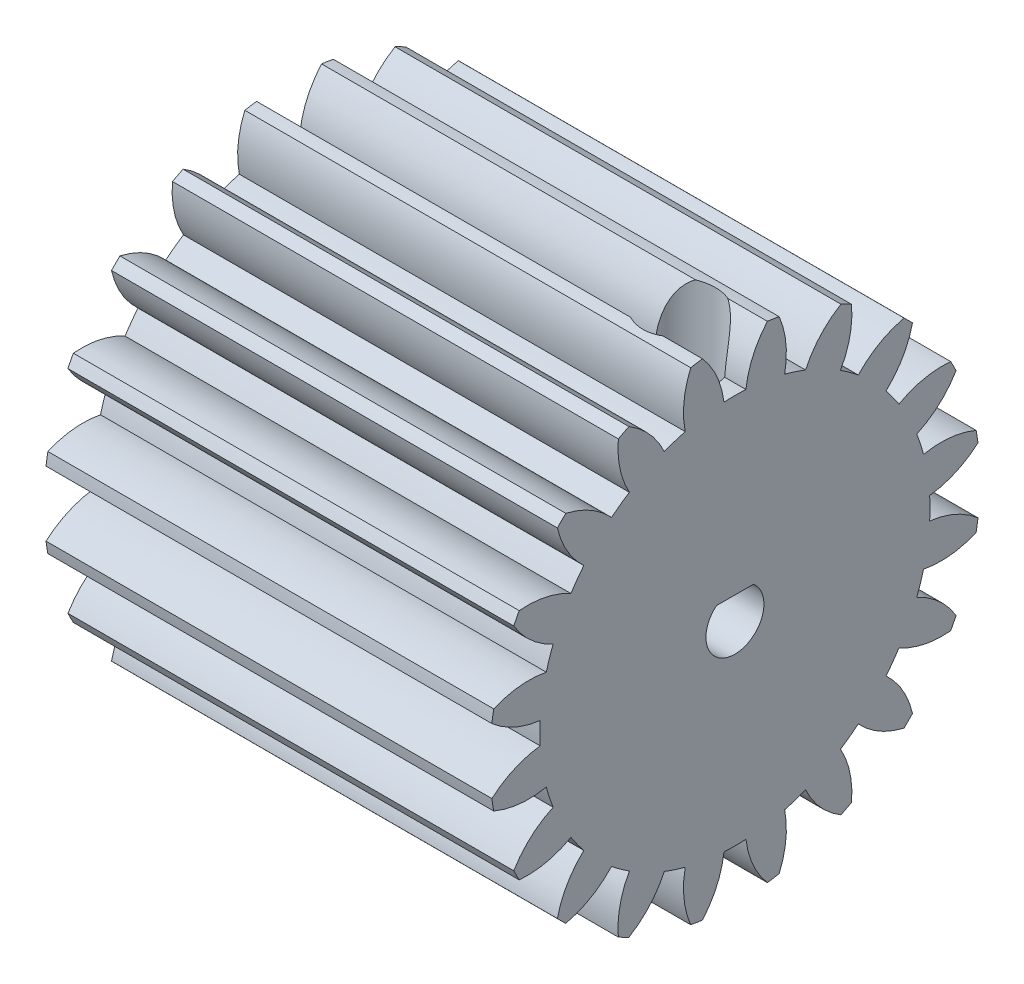
SolidWorks part; units mm, degrees
ref_plane "Plane1" through (0, 0, 0) normal (0, 0, 1) x (1, 0, 0)
ref_plane "Plane2" through (0, 0, 0) normal (0, 1, 0) x (1, 0, 0)
ref_plane "Plane3" through (0, 0, 0) normal (1, 0, 0) x (0, 0, -1)
other "Configuration Table"
sketch "HoldingSke" plane through (0, 0, 0) normal (0, 1, 0) x (1, 0, 0)
  line L0 (0, 0) -> (0.4698, -0.171)
  line L1 (-15, 0) -> (100, 0) construction
  line L2 (0, 0) -> (-2.1039, 2.3779)
  line L3 (0, 0) -> (-11.863, 4.5341)
  line L4 (0, 0) -> (8.1152, 2.9537)
  line L5 (0, 0) -> (-46.8476, -17.4728)
  line L6 (0, 0) -> (-33.1585, -22.3721)
  line L7 (-2.1039, 2.3779) -> (8.6586, 51.2059)
  line L8 (-76.2, 54.61) -> (-76.1, 54.61)
  line L9 (-71.009, 38.7566) -> (-53.1078, 45.2721)
  line L10 (-76.2, 71.12) -> (104.1128, 71.12)
  line L11 (0, 0) -> (-40, 0)
  line L12 (-76.2, 101.6) -> (-76.133, 101.6)
  line L13 (24.9733, 27.94) -> (52.9518, 28.4284)
  line L14 (24.9733, 27.94) -> (24.9743, 27.94)
  line L15 (24.9733, 27.94) -> (100.4006, 29.5858)
  line L16 (-63.627, -2) -> (-12.827, -2)
  circle A0 centre (0, 0) radius 0.4
  circle A1 centre (0, 0) radius 17.499
  circle A2 centre (0, 0) radius 37.5
  circle A3 centre (0, 0) radius 0.4
  dimension "MHD" = 34.998
  dimension "Hub_dia" = 75
  dimension "Bore" = 0.8
  dimension "MBD" = 0.8
  dimension "Num_teeth" = 20
  dimension "Pitch" = 0.5
  dimension "Overall_len" = 50
  dimension "Show_teeth" = 20
  dimension "Thickness" = 40
  dimension "OAL" = 50.0001
  dimension "T_dim" = 0.1
  dimension "Ap" = 20
  dimension "H" = 19.05
  dimension "Pitch_radius" = 180.3128
  dimension "Width" = 40
  dimension "Backlash" = 0.067
  dimension "Addendum_fac" = 1
  dimension "Dedendum_fac" = 1.25
  dimension "Clearance_fac" = 0.25
  dimension "Dedendum_add" = 0.001
  dimension "Module" = 2
sketch "BasProSke" plane through (0, 0, 0) normal (0, 1, 0) x (1, 0, 0)
  line L0 (-10, 0) -> (60, 0) construction
  line L1 (0, 0) -> (0, 22)
  line L2 (0, 0) -> (40, 0)
  line L3 (40, 0) -> (40, 22)
  line L4 (40, 22) -> (0, 22)
  dimension "Thickness" = 40
  dimension "Diameter" = 44
revolve "Base-Revolve" add sketch "BasProSke" angle 360 about L0
sketch "TooCutSke" plane through (0, 0, 0) normal (1, 0, 0) x (0, 0, -1)
  line L1 (0, 0) -> (0, 107) construction
  line L2 (0, 0) -> (-1.6864, 19.9288) construction
  line L3 (0, 0) -> (-6.2409, 39.4033) construction
  line L4 (-1.6864, 19.9288) -> (-3.1204, 19.7016) construction
  arc A0 (0.9862, 17.4712) -> (-0.9862, 17.4712) centre (0, 0) ccw
  arc A1 (2.9329, 21.8293) -> (-2.9329, 21.8293) centre (0, 0) ccw
  circle A2 centre (0, 0) radius 20 construction
  circle A3 centre (0, 0) radius 18.7939 construction
  arc A4 (-0.9862, 17.4712) -> (-2.9329, 21.8293) centre (-8.9313, 16.536) ccw
  arc A5 (2.9329, 21.8293) -> (0.9862, 17.4712) centre (8.9313, 16.536) ccw
  dimension "Root_dia" = 34.998
  dimension "Overcut_dia" = 44.0508
  dimension "Pitch_dia" = 40
  dimension "Base_dia" = 37.5877
  dimension "Flank_rad" = 8
  dimension "Half_ang" = 9
  dimension "Half_CT" = 1.4519
extrude "ToothCut" cut sketch "TooCutSke" along normal through all
fillet "Breaks" [suppressed] radius 0.04
fillet "RootFillets" [suppressed] radius 0.501
pattern_circular "TeethCuts" count 20 every 18 about axis through (-10, 0, 0) along (1, 0, 0) of "ToothCut", "RootFillets", "Breaks"
sketch "HubNeaOneSke" plane through (0, 0, 0) normal (-1, 0, 0) x (0, 0, 1)
  circle A0 centre (0, 0) radius 17.499
  dimension "Diameter" = 34.998
extrude "HubNearOne" [suppressed] add sketch "HubNeaOneSke" along normal blind 10.0001
sketch "HubNeaBotSke" plane through (0, 0, 0) normal (-1, 0, 0) x (0, 0, 1)
  circle A0 centre (0, 0) radius 17.499
  dimension "Diameter" = 34.998
extrude "HubNearBoth" [suppressed] add sketch "HubNeaBotSke" along normal blind 5
ref_plane "FarPln" through (40, 0, 0) normal (1, 0, 0) x (0, 0, -1)
sketch "HubFarSke" plane through (40, 0, 0) normal (1, 0, 0) x (0, 0, -1)
  circle A0 centre (0, 0) radius 17.499
  dimension "Diameter" = 34.998
extrude "HubFar" [suppressed] add sketch "HubFarSke" along normal blind 5
sketch "BorSke" plane through (0, 0, 0) normal (1, 0, 0) x (0, 0, -1)
  circle A0 centre (0, 0) radius 0.4
  dimension "Diameter" = 0.8
extrude "Bore" cut sketch "BorSke" along normal mid plane 100.0001
sketch "KeySke" plane through (0, 0, 0) normal (1, 0, 0) x (0, 0, -1)
  line L0 (-0.05, 0) -> (-0.05, 0.5)
  line L1 (-0.05, 0.5) -> (0.05, 0.5)
  line L2 (0.05, 0.5) -> (0.05, 0)
  line L3 (0, 0) -> (0, 34) construction
  line L4 (-0.05, 0) -> (0.05, 0)
  dimension "Offset" = 0.5
  dimension "Width" = 0.1
extrude "Keyway" [suppressed] cut sketch "KeySke" along normal mid plane 100.0001
pattern_circular "Keyway2" [suppressed] count 2 every 90 about axis through (-10, 0, 0) along (1, 0, 0)
sketch "Sketch1" plane through (40, 0, 0) normal (1, 0, 0) x (0, 0, -1)
  circle A0 centre (0, 0) radius 2.6
  dimension "D1" = 5.2
extrude "Cut-Extrude1" cut sketch "Sketch1" against normal through all
sketch "Sketch2" plane through (0, 0, 0) normal (-1, 0, 0) x (0, 0, 1)
  line L0 (-2.2361, 2) -> (2.2361, 2)
  arc A0 (2.2361, 2) -> (-2.2361, 2) centre (0, 0) ccw
  dimension "D2" = 6
  dimension "D1" = 2
extrude "Boss-Extrude1" add sketch "Sketch2" against normal up to surface (40 mm away) up to face at (40, 0, -2.6)
sketch "Sketch3" plane through (0, 0, 0) normal (-1, 0, 0) x (0, 0, 1)
  line L0 (-1.6613, 2) -> (1.6613, 2) construction
  line L1 (-1.6613, 2) -> (1.6613, 2)
  arc A0 (-1.6613, 2) -> (1.6613, 2) centre (0, 0) ccw construction
  arc A1 (-1.6613, 2) -> (1.6613, 2) centre (0, 0) ccw
extrude "Boss-Extrude2" add sketch "Sketch3" against normal blind 10
ref_plane "Plane4" through (0, 6, 0) normal (0, 1, 0) x (1, 0, 0)
sketch "Sketch4" plane through (0, 6, 0) normal (0, 1, 0) x (1, 0, 0)
  line L0 (40, 0) -> (35, 0) construction
  line L1 (40, -1.6613) -> (40, 1.6613) construction
  circle A0 centre (35, 0) radius 3.25
  dimension "D2" = 6.5
  dimension "D1" = 5
extrude "Cut-Extrude2" cut sketch "Sketch4" along normal through all
sketch "Sketch5" plane through (0, 6, 0) normal (0, 1, 0) x (1, 0, 0)
  circle A0 centre (35, 0) radius 1.4
  dimension "D1" = 2.8
extrude "Cut-Extrude3" cut sketch "Sketch5" against normal up to next
equation "' \"Module@HoldingSke\" = 6.35"
equation "' \"Num_teeth@HoldingSke\" = 12"
equation "' \"Ap@HoldingSke\" =  20"
equation "' \"Ap@HoldingSke\" = 20"
equation "' \"Width@HoldingSke\" = 0.5 * 25.4"
equation "' \"Hub_dia@HoldingSke\"= 1 * 25.4"
equation "' \"Hub_dia@HoldingSke\" = 1 * 25.4"
equation "' \"Overall_len@HoldingSke\" = 1.0 * 25.4"
equation "' \"Bore@HoldingSke\" = 0.75 * 25.4"
equation "' \"T_dim@HoldingSke\" = 0.1 * 25.4"
equation "' \"Width@KeySke\" = 0.25 * 25.4"
equation "' \"Show_teeth@HoldingSke\" = 13"
equation "' \"Backlash@HoldingSke\" = 0.009 * 25.4"
equation "' \"Addendum_fac@HoldingSke\" = 1.0"
equation "' \"Dedendum_fac@HoldingSke\" = 1.25"
equation "' \"Dedendum_add@HoldingSke\" = 0.00005 * 25.4"
equation "' \"Clearance_fac@HoldingSke\" = 0.25"
equation "\"Pitch@HoldingSke\" = 1 / \"Module@HoldingSke\""
equation "\"Overcut_dia@TooCutSke\" = (\"Num_teeth@HoldingSke\" + 2 * \"Addendum_fac@HoldingSke\") / \"Pitch@HoldingSke\" + 0.002 * 25.4"
equation "\"Pitch_dia@TooCutSke\" = \"Num_teeth@HoldingSke\" / \"Pitch@HoldingSke\""
equation "\"Base_dia@TooCutSke\" = \"Num_teeth@HoldingSke\" / \"Pitch@HoldingSke\" * cos((\"Ap@HoldingSke\"  * 3.14159265 / 180))"
equation "\"Root_dia@TooCutSke\" = (\"Num_teeth@HoldingSke\" + 2) / \"Pitch@HoldingSke\" - 2 * (\"Addendum_fac@HoldingSke\" + \"Dedendum_fac@HoldingSke\") / \"Pitch@HoldingSke\" - \"Dedendum_add@HoldingSke\" * 2"
equation "\"Half_ang@TooCutSke\" = 180 / \"Num_teeth@HoldingSke\""
equation "\"Half_CT@TooCutSke\" = \"Num_teeth@HoldingSke\" / \"Pitch@HoldingSke\" * sin((3.14159265 / 2 / \"Num_teeth@HoldingSke\")) / 2 - 7 * \"Backlash@HoldingSke\" / 4"
equation "\"Flank_rad@TooCutSke\" = \"Num_teeth@HoldingSke\" / \"Pitch@HoldingSke\" / 5"
equation "\"Radius@RootFillets\" = \"Clearance_fac@HoldingSke\" / \"Pitch@HoldingSke\" + \"Dedendum_add@HoldingSke\""
equation "\"Break_rad@Breaks\" = 0.02 / \"Pitch@HoldingSke\""
equation "\"Thickness@HoldingSke\" = \"Width@HoldingSke\""
equation "\"OAL@HoldingSke\" = \"Thickness@HoldingSke\""
equation "\"MHD@HoldingSke\" = (\"Num_teeth@HoldingSke\" + 2) / \"Pitch@HoldingSke\" - 2 * (\"Addendum_fac@HoldingSke\" + \"Dedendum_fac@HoldingSke\")  / \"Pitch@HoldingSke\" - \"Dedendum_add@HoldingSke\" * 2"
equation "\"MBD@HoldingSke\" = (\"Num_teeth@HoldingSke\" + 2) / \"Pitch@HoldingSke\" - 2 * (\"Addendum_fac@HoldingSke\" + \"Dedendum_fac@HoldingSke\")  / \"Pitch@HoldingSke\" - \"Dedendum_add@HoldingSke\" * 2 - 0.002 * 25.4"
equation "\"MHD@HoldingSke\" = ((sgn( \"MHD@HoldingSke\" - \"Hub_dia@HoldingSke\" )-1)*( \"MHD@HoldingSke\" - \"Hub_dia@HoldingSke\" ))/-2+ \"Hub_dia@HoldingSke\""
equation "\"MBD@HoldingSke\" = ((sgn( \"MBD@HoldingSke\" - \"Bore@HoldingSke\" )-1)*( \"MBD@HoldingSke\" - \"Bore@HoldingSke\" ))/-2+ \"Bore@HoldingSke\""
equation "\"OAL@HoldingSke\" = ((sgn( \"OAL@HoldingSke\" - \"Overall_len@HoldingSke\" )+1)*( \"OAL@HoldingSke\" - \"Overall_len@HoldingSke\" ))/2 + \"Overall_len@HoldingSke\" + 0.000002 * 25.4"
equation "\"Num_teeth@TeethCuts\" = int( \"Show_teeth@HoldingSke\" ) + 1"
equation "\"Num_teeth@TeethCuts\" = ((sgn( \"Num_teeth@TeethCuts\" - \"Num_teeth@HoldingSke\" )-1)*( \"Num_teeth@TeethCuts\" - \"Num_teeth@HoldingSke\" ))/-2+ \"Num_teeth@HoldingSke\""
equation "\"Num_teeth@TeethCuts\" = ((sgn( \"Num_teeth@TeethCuts\" - 2.0)+1)*( \"Num_teeth@TeethCuts\" - 2.0))/2 +2.0"
equation "\"Angle@TeethCuts\" = 360.0 / \"Num_teeth@HoldingSke\""
equation "\"Diameter@BasProSke\" = (\"Num_teeth@HoldingSke\" + 2 * \"Addendum_fac@HoldingSke\") / \"Pitch@HoldingSke\""
equation "\"Thickness@BasProSke\"  = \"Thickness@HoldingSke\""
equation "' \"Fillet_rad@BasProSke\" =  \"Thickness@HoldingSke\" * 0.05"
equation "' \"Fillet_rad@BasProSke\" = \"Thickness@HoldingSke\" * 0.05"
equation "\"MHD@HoldingSke\" = ((sgn( \"MHD@HoldingSke\" - \"Root_dia@TooCutSke\" )-1)*( \"MHD@HoldingSke\" - \"Root_dia@TooCutSke\" ))/-2+ \"Root_dia@TooCutSke\""
equation "\"Diameter@HubNeaOneSke\" = \"MHD@HoldingSke\""
equation "\"Length@HubNearOne\" = \"OAL@HoldingSke\" - \"Thickness@BasProSke\""
equation "\"Diameter@HubNeaBotSke\" = \"MHD@HoldingSke\""
equation "\"Length@HubNearBoth\" = ( \"OAL@HoldingSke\" - \"Thickness@BasProSke\" ) / 2.0"
equation "\"Thickness@FarPln\" = \"Thickness@BasProSke\""
equation "\"Diameter@HubFarSke\" = \"MHD@HoldingSke\""
equation "\"Length@HubFar\" = ( \"OAL@HoldingSke\" - \"Thickness@BasProSke\" ) / 2.0"
equation "\"Diameter@BorSke\" = \"MBD@HoldingSke\""
equation "\"D1@Bore\" = \"OAL@HoldingSke\" * 2.0"
equation "\"D1@Keyway\" = \"OAL@HoldingSke\" * 2.0"
equation "\"Offset@KeySke\" = \"T_dim@HoldingSke\" + \"MBD@HoldingSke\" / 2.0"
